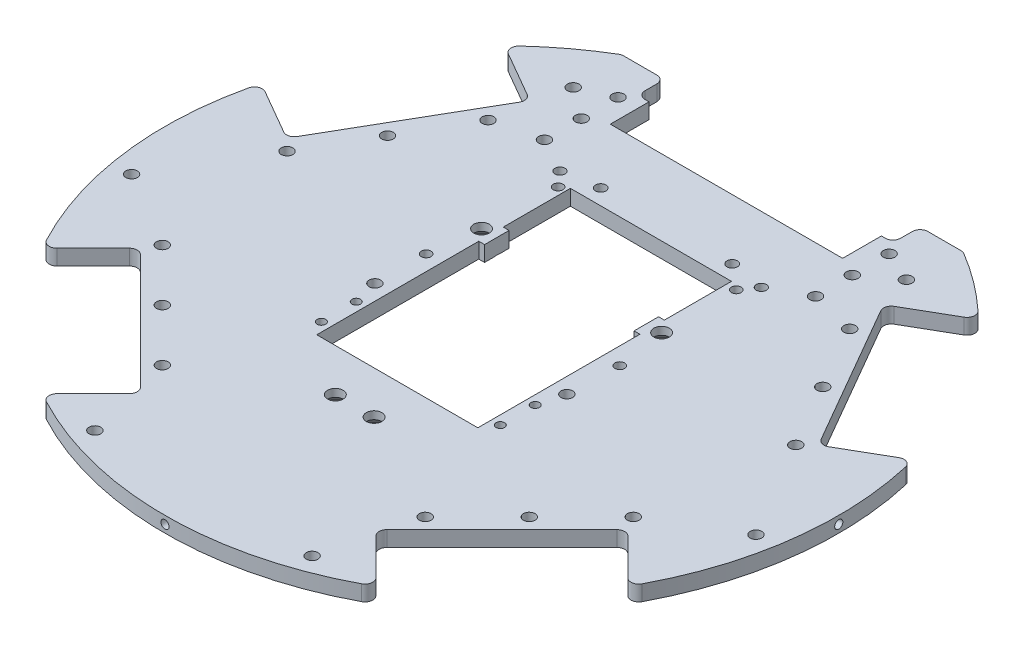
SolidWorks part; units mm, degrees
ref_plane "Front Plane" through (0, 0, 0) normal (0, 0, 1) x (1, 0, 0)
ref_plane "Top Plane" through (0, 0, 0) normal (0, 1, 0) x (1, 0, 0)
ref_plane "Right Plane" through (0, 0, 0) normal (1, 0, 0) x (0, 0, -1)
sketch "Sketch1" plane through (0, 0, 0) normal (0, 1, 0) x (1, 0, 0)
  line L0 (0, 75) -> (0, -70.0325) construction
  line L1 (0, 0) -> (57.1577, 33) construction
  line L2 (0, 0) -> (46.669, -46.669) construction
  line L3 (45.6577, 52.9186) -> (68.6577, 13.0814)
  line L4 (-44.0908, 75) -> (44.0908, 75) construction
  line L5 (62.9325, -30.4056) -> (30.4056, -62.9325)
  line L6 (45.6577, 52.9186) -> (61.1636, 61.8709)
  line L7 (68.6577, 13.0814) -> (84.1636, 22.0338)
  line L8 (30.4056, -62.9325) -> (43.0661, -75.593)
  line L9 (62.9325, -30.4056) -> (75.593, -43.0661)
  line L10 (-33, 69) -> (33, 69)
  line L11 (33, 69) -> (33, 75)
  line L12 (33, 75) -> (44.0908, 75)
  line L13 (0, 0) -> (-46.669, -46.669) construction
  line L14 (0, 0) -> (-57.1577, 33) construction
  line L15 (-33, 75) -> (-44.0908, 75)
  line L16 (-33, 69) -> (-33, 75)
  line L17 (-62.9325, -30.4056) -> (-75.593, -43.0661)
  line L18 (-30.4056, -62.9325) -> (-43.0661, -75.593)
  line L19 (-68.6577, 13.0814) -> (-84.1636, 22.0338)
  line L20 (-45.6577, 52.9186) -> (-61.1636, 61.8709)
  line L21 (-62.9325, -30.4056) -> (-30.4056, -62.9325)
  line L22 (-45.6577, 52.9186) -> (-68.6577, 13.0814)
  arc A0 (-43.0661, -75.593) -> (43.0661, -75.593) centre (0, 0) ccw
  arc A1 (61.1636, 61.8709) -> (44.0908, 75) centre (0, 0) ccw
  arc A2 (75.593, -43.0661) -> (84.1636, 22.0338) centre (0, 0) ccw
  arc A3 (-75.593, -43.0661) -> (-84.1636, 22.0338) centre (0, 0) cw
  arc A4 (-61.1636, 61.8709) -> (-44.0908, 75) centre (0, 0) cw
  point P27 (0, 69)
  dimension "D1" = 87
  dimension "D2" = 75
  dimension "D3" = 66
  dimension "D4" = 60
  dimension "D5" = 45
  dimension "D6" = 46
  dimension "D7" = 46
  dimension "D8" = 33
  dimension "D9" = 6
extrude "Boss-Extrude1" add sketch "Sketch1" along normal mid plane 4
fillet "Fillet1" radius 2 20 edges at (33, 0, -75) (-33, 0, -75) (44.0908, 0, -75) (68.6577, 0, -13.0814) (84.1636, 0, -22.0338) (45.6577, 0, -52.9186) (61.1636, 0, -61.8709) (62.9325, 0, 30.4056) (43.0661, 0, 75.593) (30.4056, 0, 62.9325) (75.593, 0, 43.0661) (-43.0661, 0, 75.593) (-30.4056, 0, 62.9325) (-75.593, 0, 43.0661) (-62.9325, 0, 30.4056) (-68.6577, 0, -13.0814) (-84.1636, 0, -22.0338) (-45.6577, 0, -52.9186) (-44.0908, 0, -75) (-61.1636, 0, -61.8709)
sketch "Sketch2" plane through (0, -2, 0) normal (0, -1, 0) x (-1, 0, 0)
  line L0 (46.6936, 43.1244) -> (65.6936, 10.2154) construction
  line L1 (60.8112, -26.8701) -> (33.9411, -53.7401) construction
  line L2 (46.6577, 51.1865) -> (67.6577, 14.8135) construction
  line L3 (61.5183, -31.8198) -> (31.8198, -61.5183) construction
  line L4 (70.3897, 14.0814) -> (81.8562, 20.7016) construction
  line L5 (73.7091, -41.1822) -> (64.3467, -31.8198) construction
  line L6 (35, 65) -> (35, 46) construction
  line L7 (26, 61) -> (26, 41) construction
  line L8 (35, 75) -> (43.5431, 75) construction
  line L9 (-33, 69) -> (33, 69) construction
  line L10 (-33, 69) -> (33, 69) construction
  line L11 (0, 69) -> (0, -87) construction
  line L12 (-26, 61) -> (-26, 41) construction
  line L13 (-35, 65) -> (-35, 46) construction
  line L14 (-60.8112, -26.8701) -> (-33.9411, -53.7401) construction
  line L15 (-46.6936, 43.1244) -> (-65.6936, 10.2154) construction
  arc A0 (-40.7037, -76.8909) -> (40.7037, -76.8909) centre (0, 0) ccw construction
  point P0 (46.6936, 43.1244)
  point P1 (56.1936, 26.6699)
  point P2 (65.6936, 10.2154)
  point P3 (60.8112, -26.8701)
  point P4 (47.3762, -40.3051)
  point P5 (33.9411, -53.7401)
  point P18 (35, 65)
  point P19 (35, 55.5)
  point P20 (35, 46)
  point P21 (26, 61)
  point P22 (26, 41)
  point P29 (0, 69)
  point P34 (0, 69)
  point P48 (-35, 55.5)
  point P49 (-47.3762, -40.3051)
  point P50 (-56.1936, 26.6699)
  dimension "D1" = 38
  dimension "D2" = 38
  dimension "D3" = 4
  dimension "D4" = 4
  dimension "D5" = 18
  dimension "D6" = 18
  dimension "D7" = 19
  dimension "D8" = 35
  dimension "10" = 10
  dimension "D9" = 20
  dimension "D10" = 8
  dimension "D11" = 26
hole_wizard "CSK for M3 SFHCS1" positions "3DSketch1" profile "Sketch3" countersink size "M3" standard "ANSI Metric"
sketch3d "3DSketch1"
  point P0 (46.6936, -2, -43.1244)
  point P3 (56.1936, -2, -26.6699)
  point P6 (65.6936, -2, -10.2154)
  point P9 (60.8112, -2, 26.8701)
  point P12 (47.3762, -2, 40.3051)
  point P15 (33.9411, -2, 53.7401)
  point P18 (-33.9411, -2, 53.7401)
  point P21 (-47.3762, -2, 40.3051)
  point P24 (-60.8112, -2, 26.8701)
  point P27 (-46.6936, -2, -43.1244)
  point P30 (-56.1936, -2, -26.6699)
  point P33 (-65.6936, -2, -10.2154)
  point P36 (-35, -2, -65)
  point P39 (-35, -2, -55.5)
  point P42 (-35, -2, -46)
  point P45 (35, -2, -46)
  point P48 (35, -2, -55.5)
  point P51 (35, -2, -65)
sketch "Sketch3" plane through (46.6936, -2, -43.1244) normal (1, 0, 0) x (0, 0, -1)
  line L0 (0, 0) -> (0, 10.4013)
  line L1 (0, 10.4013) -> (1.5, 9.5)
  line L2 (1.5, 9.5) -> (1.5, 1.3)
  line L3 (1.5, 1.3) -> (2.8, 0)
  line L5 (2.8, 0) -> (0, 0)
  line L6 (-1.5, 1.3) -> (-2.8, 0) construction
  line L10 (0, 10.4013) -> (-1.5, 9.5) construction
  line L11 (0, -6.35) -> (0, 107.95) construction
  dimension "Hole Dia." = 3
  dimension "Hole Depth" = 9.5
  dimension "Near C'Sink Dia." = 5.6
  dimension "Near C'Sink Angle" = 90
  dimension "Drill Angle" = 118
sketch "Sketch4" plane through (0, -2, 0) normal (0, -1, 0) x (1, 0, 0)
  line L0 (0, 0) -> (-43.0182, -61.4364) construction
  line L1 (0, 0) -> (-28.0457, 77.0548) construction
  line L2 (0, -69) -> (0, 87) construction
  line L3 (0, 0) -> (-80.6164, 15) construction
  line L4 (0, -69) -> (0, 87) construction
  line L5 (0, 0) -> (80.6164, 15) construction
  line L6 (0, 0) -> (28.0457, 77.0548) construction
  line L7 (0, 0) -> (43.0182, -61.4364) construction
  dimension "D1" = 75
  dimension "D2" = 35
  dimension "D3" = 82
  dimension "D4" = 20
  dimension "D5" = 82
  dimension "D6" = 15
hole_wizard "CSK for M3 SFHCS2" positions "3DSketch2" profile "Sketch5" countersink size "M3" standard "ANSI Metric"
sketch3d "3DSketch2"
  point P0 (43.0182, -2, -61.4364)
  point P3 (80.6164, -2, 15)
  point P6 (28.0457, -2, 77.0548)
  point P9 (-28.0457, -2, 77.0548)
  point P12 (-80.6164, -2, 15)
  point P15 (-43.0182, -2, -61.4364)
sketch "Sketch5" plane through (43.0182, -2, -61.4364) normal (1, 0, 0) x (0, 0, -1)
  line L0 (0, 0) -> (0, 10.4013)
  line L1 (0, 10.4013) -> (1.5, 9.5)
  line L2 (1.5, 9.5) -> (1.5, 1.3)
  line L3 (1.5, 1.3) -> (2.8, 0)
  line L5 (2.8, 0) -> (0, 0)
  line L6 (-1.5, 1.3) -> (-2.8, 0) construction
  line L10 (0, 10.4013) -> (-1.5, 9.5) construction
  line L11 (0, -6.35) -> (0, 107.95) construction
  dimension "Hole Dia." = 3
  dimension "Hole Depth" = 9.5
  dimension "Near C'Sink Dia." = 5.6
  dimension "Near C'Sink Angle" = 90
  dimension "Drill Angle" = 118
hole_wizard "CSK for M3 SFHCS3" positions "3DSketch3" profile "Sketch6" countersink size "M3" standard "ANSI Metric"
sketch3d "3DSketch3"
  point P0 (26, -2, -41)
  point P3 (26, -2, -61)
  point P6 (-26, -2, -41)
  point P9 (-26, -2, -61)
sketch "Sketch6" plane through (26, -2, -41) normal (1, 0, 0) x (0, 0, -1)
  line L0 (0, 0) -> (0, 10.2811)
  line L1 (0, 10.2811) -> (1.3, 9.5)
  line L2 (1.3, 9.5) -> (1.3, 1)
  line L3 (1.3, 1) -> (2.3, 0)
  line L5 (2.3, 0) -> (0, 0)
  line L6 (-1.3, 1) -> (-2.3, 0) construction
  line L10 (0, 10.2811) -> (-1.3, 9.5) construction
  line L11 (0, -6.35) -> (0, 107.95) construction
  dimension "Hole Dia." = 2.6
  dimension "Hole Depth" = 9.5
  dimension "Near C'Sink Dia." = 4.6
  dimension "Near C'Sink Angle" = 90
  dimension "Drill Angle" = 118
sketch "Sketch7" plane through (0, 0, 0) normal (0, 1, 0) x (1, 0, 0)
  arc A0 (-84.8058, 19.4159) -> (-76.8909, -40.7037) centre (0, 0) ccw construction
  arc A1 (76.8909, -40.7037) -> (84.8058, 19.4159) centre (0, 0) ccw construction
  arc A2 (-40.7037, -76.8909) -> (40.7037, -76.8909) centre (0, 0) ccw construction
  arc A3 (59.2176, 63.736) -> (44.5676, 74.7176) centre (0, 0) ccw construction
  arc A4 (-44.5676, 74.7176) -> (-59.2176, 63.736) centre (0, 0) ccw construction
  point P0 (-86.2557, -11.3558)
  point P1 (86.2557, -11.3558)
  point P5 (0, -87)
  point P9 (52.1823, 69.6133)
  point P13 (-52.1823, 69.6133)
ref_plane "Plane1" through (87, 0, 0) normal (1, 0, 0) x (0, 0, -1)
sketch "Sketch9" plane through (87, 0, 0) normal (1, 0, 0) x (0, 0, -1)
  circle A0 centre (0, 0) radius 1.05
  dimension "D1" = 2.1
ref_plane "Plane2" through (0, 0, 87) normal (0, 0, 1) x (1, 0, 0)
sketch "Sketch10" plane through (0, 0, 87) normal (0, 0, 1) x (1, 0, 0)
  circle A0 centre (0, 0) radius 1.05
  dimension "D1" = 2.1
ref_plane "Plane3" through (52.1823, 0, -69.6133) normal (0.5998, 0, -0.8002) x (-0.8002, 0, -0.5998)
sketch "Sketch11" plane through (52.1823, 0, -69.6133) normal (0.5998, 0, -0.8002) x (-0.8002, 0, -0.5998)
  circle A0 centre (0, 0) radius 1.05
  dimension "D1" = 2.1
sketch "Sketch12" plane through (0, 2, 0) normal (0, 1, 0) x (1, 0, 0)
  line L0 (-23.25, 18) -> (23.25, 18) construction
  line L1 (24.78, -8) -> (-24.78, -8) construction
  line L2 (-5, -38) -> (5, -38) construction
  line L3 (33, 69) -> (-33, 69) construction
  line L4 (-35, 75) -> (-43.5431, 75) construction
  point P0 (-23.25, 18)
  point P1 (23.25, 18)
  point P2 (-5, -38)
  point P3 (5, -38)
  point P4 (-24.78, -8)
  point P5 (24.78, -8)
  point P14 (0, 18)
  point P16 (0, -8)
  point P17 (0, -38)
  dimension "D1" = 51
  dimension "D2" = 83
  dimension "D3" = 56
  dimension "D4" = 49.56
  dimension "D5" = 10
  dimension "D6" = 46.5
sketch "Sketch14" plane through (0, -2, 0) normal (0, -1, 0) x (1, 0, 0)
  point P0 (23.25, -18)
  point P1 (-23.25, -18)
  point P3 (-24.78, 8)
  point P5 (24.78, 8)
  point P7 (5, 38)
  point P9 (-5, 38)
hole_wizard "CSK for M4 SFHCS3" positions "3DSketch7" profile "Sketch16" countersink size "M4" standard "ANSI Metric"
sketch3d "3DSketch7"
  point P0 (23.25, -2, -18)
  point P3 (-23.25, -2, -18)
  point P6 (-5, -2, 38)
  point P9 (5, -2, 38)
sketch "Sketch16" plane through (23.25, -2, -18) normal (1, 0, 0) x (0, 0, -1)
  line L0 (0, 0) -> (0, 10.7017)
  line L1 (0, 10.7017) -> (2, 9.5)
  line L2 (2, 9.5) -> (2, 2)
  line L3 (2, 2) -> (4, 0)
  line L5 (4, 0) -> (0, 0)
  line L6 (-2, 2) -> (-4, 0) construction
  line L10 (0, 10.7017) -> (-2, 9.5) construction
  line L11 (0, -6.35) -> (0, 107.95) construction
  dimension "Hole Dia." = 4
  dimension "Hole Depth" = 9.5
  dimension "Near C'Sink Dia." = 8
  dimension "Near C'Sink Angle" = 90
  dimension "Drill Angle" = 118
hole_wizard "CSK for M3 SFHCS4" positions "3DSketch8" profile "Sketch17" countersink size "M3" standard "ANSI Metric"
sketch3d "3DSketch8"
  point P0 (24.78, -2, 8)
  point P3 (-24.78, -2, 8)
sketch "Sketch17" plane through (24.78, -2, 8) normal (1, 0, 0) x (0, 0, -1)
  line L0 (0, 0) -> (0, 10.4013)
  line L1 (0, 10.4013) -> (1.5, 9.5)
  line L2 (1.5, 9.5) -> (1.5, 1.3)
  line L3 (1.5, 1.3) -> (2.8, 0)
  line L5 (2.8, 0) -> (0, 0)
  line L6 (-1.5, 1.3) -> (-2.8, 0) construction
  line L10 (0, 10.4013) -> (-1.5, 9.5) construction
  line L11 (0, -6.35) -> (0, 107.95) construction
  dimension "Hole Dia." = 3
  dimension "Hole Depth" = 9.5
  dimension "Near C'Sink Dia." = 5.6
  dimension "Near C'Sink Angle" = 90
  dimension "Drill Angle" = 118
extrude "Cut-Extrude1" cut sketch "Sketch9" against normal blind 8
extrude "Cut-Extrude2" cut sketch "Sketch10" against normal blind 8
extrude "Cut-Extrude3" cut sketch "Sketch11" against normal blind 8
mirror "Mirror1" about plane through (0, 0, 0) normal (1, 0, 0) of "Cut-Extrude3", "Cut-Extrude2", "Cut-Extrude1"
sketch "Sketch18" plane through (0, 2, 0) normal (0, 1, 0) x (1, 0, 0)
  line L0 (-44.8999, 78) -> (44.8999, 78) construction
  line L1 (-35, 75) -> (-43.5431, 75) construction
  circle A0 centre (0, 0) radius 90 construction
  dimension "D1" = 180
  dimension "D2" = 3
hole_wizard "M2.5x0.45 Tapped Hole1" positions "3DSketch9" profile "Sketch19" tap size "M2.5x0.45" standard "ANSI Metric"
sketch3d "3DSketch9"
  line L0 (-35, 2, -75) -> (-43.5431, 2, -75) construction
  line L1 (43.5431, 2, -75) -> (35, 2, -75) construction
  line L2 (-35, -2, -75) -> (-43.5431, -2, -75) construction
  point P0 (-39.2715, 0, -75)
  point P2 (39.4456, 0, -75)
  point P11 (-39.2715, -2, -75)
  dimension "D1" = 2
  dimension "D2" = 2
sketch "Sketch19" plane through (-39.2715, 0, -75) normal (1, 0, 0) x (0, 1, 0)
  line L0 (0, 0) -> (0, 6.9659)
  line L1 (0, 6.9659) -> (1.025, 6.35)
  line L2 (1.025, 6.35) -> (1.025, 0)
  line L5 (1.025, 0) -> (0, 0)
  line L10 (0, 6.9659) -> (-1.025, 6.35) construction
  line L11 (0, -6.35) -> (0, 107.95) construction
  dimension "Tap Drill Dia." = 2.05
  dimension "Tap Drill Depth" = 6.35
  dimension "Drill Angle" = 118
sketch "Sketch21" plane through (0, 2, 0) normal (0, 1, 0) x (1, 0, 0)
  line L17 (43.5431, 75) -> (35, 75)
  line L18 (33, 73) -> (33, 69)
  line L19 (33, 69) -> (-33, 69)
  line L20 (-33, 69) -> (-33, 73)
  line L21 (-35, 75) -> (-43.5431, 75)
  line L22 (-58.8562, 60.5388) -> (-47.3897, 53.9186)
  line L23 (-46.6577, 51.1865) -> (-67.6577, 14.8135)
  line L24 (-70.3897, 14.0814) -> (-81.8562, 20.7016)
  line L25 (-73.7091, -41.1822) -> (-64.3467, -31.8198)
  line L26 (-61.5183, -31.8198) -> (-31.8198, -61.5183)
  line L27 (-31.8198, -64.3467) -> (-41.1822, -73.7091)
  line L28 (41.1822, -73.7091) -> (31.8198, -64.3467)
  line L29 (31.8198, -61.5183) -> (61.5183, -31.8198)
  line L30 (64.3467, -31.8198) -> (73.7091, -41.1822)
  line L31 (81.8562, 20.7016) -> (70.3897, 14.0814)
  line L32 (67.6577, 14.8135) -> (46.6577, 51.1865)
  line L33 (47.3897, 53.9186) -> (58.8562, 60.5388)
  line L34 (43.5431, 75) -> (35, 75)
  line L35 (33, 73) -> (33, 69)
  line L36 (33, 69) -> (-33, 69)
  line L37 (-33, 69) -> (-33, 73)
  line L38 (-35, 75) -> (-43.5431, 75)
  line L39 (-58.8562, 60.5388) -> (-47.3897, 53.9186)
  line L40 (-46.6577, 51.1865) -> (-67.6577, 14.8135)
  line L41 (-70.3897, 14.0814) -> (-81.8562, 20.7016)
  line L42 (-73.7091, -41.1822) -> (-64.3467, -31.8198)
  line L43 (-61.5183, -31.8198) -> (-31.8198, -61.5183)
  line L44 (-31.8198, -64.3467) -> (-41.1822, -73.7091)
  line L45 (41.1822, -73.7091) -> (31.8198, -64.3467)
  line L46 (31.8198, -61.5183) -> (61.5183, -31.8198)
  line L47 (64.3467, -31.8198) -> (73.7091, -41.1822)
  line L48 (81.8562, 20.7016) -> (70.3897, 14.0814)
  line L49 (67.6577, 14.8135) -> (46.6577, 51.1865)
  line L50 (47.3897, 53.9186) -> (58.8562, 60.5388)
  circle A1 centre (25.24, 5.2127) radius 1.25
  circle A2 centre (25.24, 5.2127) radius 1.25
  circle A3 centre (-24.76, 5.2127) radius 1.25
  circle A4 centre (-24.76, 5.2127) radius 1.25
  circle A5 centre (-22.685, 37.2127) radius 1.25
  circle A6 centre (-22.685, 37.2127) radius 1.25
  circle A7 centre (23.315, 37.2127) radius 1.25
  circle A8 centre (23.315, 37.2127) radius 1.25
  arc A27 (35, 75) -> (33, 73) centre (35, 73) ccw
  arc A30 (-33, 73) -> (-35, 75) centre (-35, 73) ccw
  arc A31 (-43.5431, 75) -> (-44.5676, 74.7176) centre (-43.5431, 73) ccw
  arc A32 (-44.5676, 74.7176) -> (-59.2176, 63.736) centre (0, 0) ccw
  arc A33 (-59.2176, 63.736) -> (-58.8562, 60.5388) centre (-57.8562, 62.2708) ccw
  arc A34 (-46.6577, 51.1865) -> (-47.3897, 53.9186) centre (-48.3897, 52.1865) ccw
  arc A35 (-70.3897, 14.0814) -> (-67.6577, 14.8135) centre (-69.3897, 15.8135) ccw
  arc A36 (-81.8562, 20.7016) -> (-84.8058, 19.4159) centre (-82.8562, 18.9696) ccw
  arc A37 (-84.8058, 19.4159) -> (-76.8909, -40.7037) centre (0, 0) ccw
  arc A38 (-76.8909, -40.7037) -> (-73.7091, -41.1822) centre (-75.1233, -39.768) ccw
  arc A39 (-61.5183, -31.8198) -> (-64.3467, -31.8198) centre (-62.9325, -33.234) ccw
  arc A40 (-31.8198, -64.3467) -> (-31.8198, -61.5183) centre (-33.234, -62.9325) ccw
  arc A41 (-41.1822, -73.7091) -> (-40.7037, -76.8909) centre (-39.768, -75.1233) ccw
  arc A42 (-40.7037, -76.8909) -> (40.7037, -76.8909) centre (0, 0) ccw
  arc A43 (40.7037, -76.8909) -> (41.1822, -73.7091) centre (39.768, -75.1233) ccw
  arc A44 (31.8198, -61.5183) -> (31.8198, -64.3467) centre (33.234, -62.9325) ccw
  arc A45 (64.3467, -31.8198) -> (61.5183, -31.8198) centre (62.9325, -33.234) ccw
  arc A46 (73.7091, -41.1822) -> (76.8909, -40.7037) centre (75.1233, -39.768) ccw
  arc A47 (76.8909, -40.7037) -> (84.8058, 19.4159) centre (0, 0) ccw
  arc A48 (84.8058, 19.4159) -> (81.8562, 20.7016) centre (82.8562, 18.9696) ccw
  arc A49 (67.6577, 14.8135) -> (70.3897, 14.0814) centre (69.3897, 15.8135) ccw
  arc A50 (47.3897, 53.9186) -> (46.6577, 51.1865) centre (48.3897, 52.1865) ccw
  arc A51 (58.8562, 60.5388) -> (59.2176, 63.736) centre (57.8562, 62.2708) ccw
  arc A52 (59.2176, 63.736) -> (44.5676, 74.7176) centre (0, 0) ccw
  arc A53 (44.5676, 74.7176) -> (43.5431, 75) centre (43.5431, 73) ccw
  arc A54 (35, 75) -> (33, 73) centre (35, 73) ccw
  arc A57 (-33, 73) -> (-35, 75) centre (-35, 73) ccw
  arc A58 (-43.5431, 75) -> (-44.5676, 74.7176) centre (-43.5431, 73) ccw
  arc A59 (-44.5676, 74.7176) -> (-59.2176, 63.736) centre (0, 0) ccw
  arc A60 (-59.2176, 63.736) -> (-58.8562, 60.5388) centre (-57.8562, 62.2708) ccw
  arc A61 (-46.6577, 51.1865) -> (-47.3897, 53.9186) centre (-48.3897, 52.1865) ccw
  arc A62 (-70.3897, 14.0814) -> (-67.6577, 14.8135) centre (-69.3897, 15.8135) ccw
  arc A63 (-81.8562, 20.7016) -> (-84.8058, 19.4159) centre (-82.8562, 18.9696) ccw
  arc A64 (-84.8058, 19.4159) -> (-76.8909, -40.7037) centre (0, 0) ccw
  arc A65 (-76.8909, -40.7037) -> (-73.7091, -41.1822) centre (-75.1233, -39.768) ccw
  arc A66 (-61.5183, -31.8198) -> (-64.3467, -31.8198) centre (-62.9325, -33.234) ccw
  arc A67 (-31.8198, -64.3467) -> (-31.8198, -61.5183) centre (-33.234, -62.9325) ccw
  arc A68 (-41.1822, -73.7091) -> (-40.7037, -76.8909) centre (-39.768, -75.1233) ccw
  arc A69 (-40.7037, -76.8909) -> (40.7037, -76.8909) centre (0, 0) ccw
  arc A70 (40.7037, -76.8909) -> (41.1822, -73.7091) centre (39.768, -75.1233) ccw
  arc A71 (31.8198, -61.5183) -> (31.8198, -64.3467) centre (33.234, -62.9325) ccw
  arc A72 (64.3467, -31.8198) -> (61.5183, -31.8198) centre (62.9325, -33.234) ccw
  arc A73 (73.7091, -41.1822) -> (76.8909, -40.7037) centre (75.1233, -39.768) ccw
  arc A74 (76.8909, -40.7037) -> (84.8058, 19.4159) centre (0, 0) ccw
  arc A75 (84.8058, 19.4159) -> (81.8562, 20.7016) centre (82.8562, 18.9696) ccw
  arc A76 (67.6577, 14.8135) -> (70.3897, 14.0814) centre (69.3897, 15.8135) ccw
  arc A77 (47.3897, 53.9186) -> (46.6577, 51.1865) centre (48.3897, 52.1865) ccw
  arc A78 (58.8562, 60.5388) -> (59.2176, 63.736) centre (57.8562, 62.2708) ccw
  arc A79 (59.2176, 63.736) -> (44.5676, 74.7176) centre (0, 0) ccw
  arc A80 (44.5676, 74.7176) -> (43.5431, 75) centre (43.5431, 73) ccw
  dimension "D1" = 0
  dimension "D2" = 0
  dimension "D3" = 0
  dimension "D4" = 0
  dimension "D5" = 0
extrude "Cut-Extrude4" cut sketch "Sketch21" against normal up to next contours A2 | A8 | A4 | A6
sketch "Sketch23" plane through (0, 0, -69) normal (0, 0, -1) x (-1, 0, 0)
  line L1 (33, -2) -> (-33, -2)
  line L2 (33, -2) -> (33, 2)
  line L3 (33, 2) -> (-33, 2)
  line L4 (-33, -2) -> (-33, 2)
extrude "Cut-Extrude6" cut sketch "Sketch23" against normal blind 1
fillet "Fillet2" radius 2 2 edges at (33, 0, -68) (-33, 0, -68)
sketch "Sketch24" plane through (0, -2, 0) normal (0, -1, 0) x (1, 0, 0)
  line L0 (31, -68) -> (-31, -68) construction
  line L1 (-20.8, 27) -> (20.8, 27)
  line L2 (-20.8, 27) -> (-20.8, -14.8381)
  line L3 (-20.8, -38.5) -> (20.8, -38.5)
  line L4 (20.8, 27) -> (20.8, -14.8381)
  line L5 (-20.8, -14.8381) -> (-19.3, -14.8381)
  line L6 (-19.3, -14.8381) -> (-19.3, -21.1619)
  line L7 (-19.3, -21.1619) -> (-20.8, -21.1619)
  line L8 (-20.8, -21.1619) -> (-20.8, -38.5)
  line L9 (20.8, -14.8381) -> (19.3, -14.8381)
  line L10 (19.3, -14.8381) -> (19.3, -21.1619)
  line L11 (19.3, -21.1619) -> (20.8, -21.1619)
  line L12 (20.8, -21.1619) -> (20.8, -38.5)
  circle A0 centre (-23.25, -18) radius 4 construction
  circle A1 centre (23.25, -18) radius 4 construction
  point P6 (0, -68)
  point P7 (0, 27)
  dimension "D1" = 29.5
  dimension "D2" = 41.6
  dimension "D3" = 65.5
  dimension "D4" = 1.5
  dimension "D5" = 1.5
extrude "Cut-Extrude9" cut sketch "Sketch24" against normal blind 10 contours L2 L5 L6 L7 L8 L3 L12 L11 L10 L9 L4 L1
sketch "Sketch25" plane through (0, 0, -68) normal (0, 0, -1) x (-1, 0, 0)
  line L0 (31, 2) -> (-31, 2) construction
  line L1 (-30, 2) -> (30, 2)
  line L2 (-30, 2) -> (-30, -2)
  line L3 (-30, -2) -> (30, -2)
  line L4 (30, 2) -> (30, -2)
  line L5 (-31, -2) -> (31, -2) construction
  line L6 (-31, 2) -> (-31, -2) construction
  line L7 (31, -2) -> (31, 2) construction
  dimension "D1" = 1
  dimension "D2" = 1
extrude "Cut-Extrude10" cut sketch "Sketch25" against normal blind 10
hole_wizard "CSK for M2 Flat Head Machine Screw2" positions "Sketch28" profile "Sketch29" countersink size "M2" standard "ANSI Metric"
sketch "Sketch28" plane through (0, -2, 0) normal (0, -1, 0) x (-1, 0, 0)
  point P0 (23.1, -23.5)
  point P2 (23.1, -14.5)
  point P4 (-23.1, -23.5)
  point P6 (-23.1, -14.5)
sketch "Sketch29" plane through (-23.1, -2, 23.5) normal (1, 0, 0) x (0, 0, -1)
  line L0 (0, 0) -> (0, 10.1609)
  line L1 (0, 10.1609) -> (1.1, 9.5)
  line L2 (1.1, 9.5) -> (1.1, 1.1)
  line L3 (1.1, 1.1) -> (2.2, 0)
  line L5 (2.2, 0) -> (0, 0)
  line L6 (-1.1, 1.1) -> (-2.2, 0) construction
  line L10 (0, 10.1609) -> (-1.1, 9.5) construction
  line L11 (0, -6.35) -> (0, 107.95) construction
  dimension "Hole Dia." = 2.2
  dimension "Hole Depth" = 9.5
  dimension "Near C'Sink Dia." = 4.4
  dimension "Near C'Sink Angle" = 90
  dimension "Drill Angle" = 118
hole_wizard "CSK for M2.5 Flat Head Machine Screw1" positions "Sketch30" profile "Sketch31" countersink size "M2.5" standard "ANSI Metric"
sketch "Sketch30" plane through (0, -2, 0) normal (0, -1, 0) x (-1, 0, 0)
  point P0 (16.975, 42.5)
  point P2 (-16.975, 42.5)
sketch "Sketch31" plane through (-16.975, -2, -42.5) normal (1, 0, 0) x (0, 0, -1)
  line L0 (0, 0) -> (0, 10.3112)
  line L1 (0, 10.3112) -> (1.35, 9.5)
  line L2 (1.35, 9.5) -> (1.35, 1.4)
  line L3 (1.35, 1.4) -> (2.75, 0)
  line L5 (2.75, 0) -> (0, 0)
  line L6 (-1.35, 1.4) -> (-2.75, 0) construction
  line L10 (0, 10.3112) -> (-1.35, 9.5) construction
  line L11 (0, -6.35) -> (0, 107.95) construction
  dimension "Hole Dia." = 2.7
  dimension "Hole Depth" = 9.5
  dimension "Near C'Sink Dia." = 5.5
  dimension "Near C'Sink Angle" = 90
  dimension "Drill Angle" = 118
